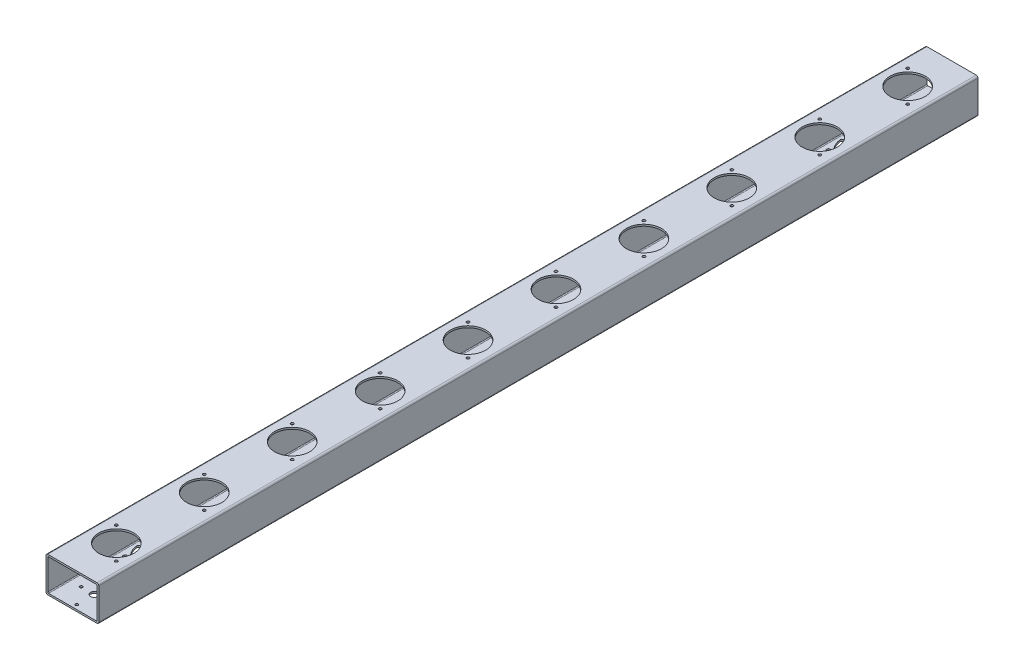
SolidWorks part; units mm, degrees
ref_plane "Plan de face" through (0, 0, 0) normal (0, 0, 1) x (1, 0, 0)
ref_plane "Plan de dessus" through (0, 0, 0) normal (0, 1, 0) x (1, 0, 0)
ref_plane "Plan de droite" through (0, 0, 0) normal (1, 0, 0) x (0, 0, -1)
sketch "Esquisse1" plane through (0, 0, 0) normal (0, 0, 1) x (1, 0, 0)
  line L0 (2, 2) -> (58, 2)
  line L1 (0, 0) -> (60, 0)
  line L2 (0, 0) -> (0, 40)
  line L3 (0, 40) -> (60, 40)
  line L4 (60, 0) -> (60, 40)
  line L5 (58, 2) -> (58, 38)
  line L6 (2, 38) -> (58, 38)
  line L7 (2, 2) -> (2, 38)
  dimension "D1" = 60
  dimension "D2" = 40
  dimension "D3" = 2
extrude "Boss.-Extru.1" add sketch "Esquisse1" along normal blind 1000
fillet "Congé1" radius 1 4 edges at (58, 2, 500) (58, 38, 500) (2, 38, 500) (2, 2, 500)
fillet "Congé2" radius 2 4 edges at (60, 0, 500) (0, 0, 500) (60, 40, 500) (0, 40, 500)
sketch "Esquisse2" plane through (0, 40, 0) normal (0, 1, 0) x (1, 0, 0)
  line L0 (30, 0) -> (30, -50) construction
  line L1 (58, 0) -> (2, 0) construction
  circle A0 centre (30, -50) radius 20
  circle A1 centre (30, -150) radius 20
  circle A2 centre (30, -250) radius 20
  circle A3 centre (30, -350) radius 20
  circle A4 centre (30, -450) radius 20
  circle A5 centre (30, -550) radius 20
  circle A6 centre (30, -650) radius 20
  circle A7 centre (30, -750) radius 20
  circle A8 centre (30, -850) radius 20
  circle A9 centre (30, -950) radius 20
  dimension "D1" = 40
  dimension "D2" = 50
  dimension "D4" = 100
  dimension "D3" = 10
extrude "Enlèv. mat.-Extru.1" cut sketch "Esquisse2" against normal up to next
sketch "Esquisse3" plane through (0, 0, 0) normal (0, -1, 0) x (1, 0, 0)
  line L0 (30, 975) -> (30, 1000) construction
  line L1 (2, 1000) -> (58, 1000) construction
  line L2 (30, 25) -> (30, 0) construction
  line L3 (2, 0) -> (58, 0) construction
  line L4 (30, 975) -> (30, 25) construction
  circle A0 centre (30, 975) radius 4.25
  circle A1 centre (30, 25) radius 4.25
  circle A2 centre (30, 500) radius 4.25
  dimension "D2" = 8.5
  dimension "D1" = 25
extrude "Enlèv. mat.-Extru.2" cut sketch "Esquisse3" against normal up to next
sketch "Esquisse4" plane through (0, 40, 0) normal (0, 1, 0) x (1, 0, 0)
  line L0 (12.3223, -32.3223) -> (47.6777, -67.6777) construction
  line L1 (2, 0) -> (2, -1000) construction
  circle A0 centre (30, -50) radius 25 construction
  circle A1 centre (30, -50) radius 20 construction
  circle A2 centre (12.3223, -32.3223) radius 1.6
  circle A3 centre (47.6777, -67.6777) radius 1.6
  point P6 (30, -50)
  dimension "D1" = 50
  dimension "D3" = 3.2
  dimension "D2" = 45
extrude "Enlèv. mat.-Extru.3" cut sketch "Esquisse4" against normal up to next
sketch "Esquisse6" plane through (0, 0, 0) normal (0, -1, 0) x (-1, 0, 0)
  line L0 (-20, -400) -> (-40, -400) construction
  line L1 (0, -400) -> (-20, -400) construction
  line L3 (0, 0) -> (0, -1000) construction
  line L4 (-40, -400) -> (-60, -400) construction
  line L5 (-60, -1000) -> (-60, 0) construction
  line L6 (-30, -370) -> (-30, -400) construction
  line L7 (-30, -400) -> (-30, -430) construction
  circle A0 centre (-20, -400) radius 1.6
  circle A1 centre (-40, -400) radius 1.6
  circle A2 centre (-30, -350) radius 20 construction
  circle A3 centre (-30, -450) radius 20 construction
  dimension "D2" = 3.2
  dimension "D1" = 20
extrude "Enlèv. mat.-Extru.4" cut sketch "Esquisse6" against normal up to next
pattern_linear "Répétition linéaire1" count 3 spacing 200 along (0, 0, 1) count 2 spacing 200 along (0, 0, -1) of "Enlèv. mat.-Extru.4"
sketch "Esquisse7" plane through (0, 0, 0) normal (0, -1, 0) x (-1, 0, 0)
  line L0 (-15, -500) -> (-45, -500) construction
  line L1 (-15, -975) -> (-45, -975) construction
  line L2 (-15, -25) -> (-45, -25) construction
  circle A0 centre (-15, -25) radius 1.6
  circle A1 centre (-45, -25) radius 1.6
  circle A2 centre (-15, -500) radius 1.6
  circle A3 centre (-45, -500) radius 1.6
  circle A4 centre (-15, -975) radius 1.6
  circle A5 centre (-45, -975) radius 1.6
  point P2 (-30, -500)
  point P3 (-30, -975)
  point P7 (-30, -25)
  dimension "D1" = 3.2
  dimension "D2" = 30
extrude "Enlèv. mat.-Extru.5" cut sketch "Esquisse7" against normal up to next
pattern_linear "Répétition linéaire2" count 10 spacing 100 along (0, 0, 1) of "Enlèv. mat.-Extru.3"
sketch "Esquisse8" plane through (0, 0, 0) normal (0, -1, 0) x (-1, 0, 0)
  circle A0 centre (-38, -55.1826) radius 1.4
  circle A1 centre (-22, -55.1826) radius 1.4
  circle A2 centre (-22, -55.1826) radius 1.25 construction
  circle A3 centre (-38, -55.1826) radius 1.25 construction
  dimension "D1" = 2.8
sketch "Esquisse9" plane through (0, 0, 0) normal (0, -1, 0) x (1, 0, 0)
  circle A1 centre (30, 950) radius 9.5306 construction
  circle A2 centre (30, 950) radius 20 construction
  circle A3 centre (22, 955.18) radius 1.1
  circle A4 centre (38, 955.18) radius 1.1
  point P8 (36.7592, 956.6587)
  point P11 (24.1118, 952.6968)
  dimension "D1" = 2.2
  dimension "D2" = 5.18
  dimension "D3" = 16
extrude "Enlèv. mat.-Extru.6" cut sketch "Esquisse9" against normal up to next
pattern_linear "Répétition linéaire3" count 10 spacing 100 along (0, 0, -1) of "Enlèv. mat.-Extru.6"
sketch "Esquisse10" plane through (0, 0, 0) normal (0, -1, 0) x (1, 0, 0)
  line L0 (2, 0) -> (58, 0) construction
  line L1 (10, 80) -> (50, 80) construction
  line L2 (10, 80) -> (10, 120) construction
  line L3 (10, 120) -> (50, 120) construction
  line L4 (50, 80) -> (50, 120) construction
  line L6 (0, 100) -> (10, 100) construction
  line L7 (0, 0) -> (0, 1000) construction
  line L8 (50, 100) -> (60, 100) construction
  line L9 (60, 1000) -> (60, 0) construction
  circle A0 centre (10, 120) radius 2.1
  circle A1 centre (50, 120) radius 2.1
  circle A2 centre (50, 80) radius 2.1
  circle A3 centre (10, 80) radius 2.1
  dimension "D2" = 4.2
  dimension "D1" = 40
  dimension "D3" = 100
extrude "Enlèv. mat.-Extru.7" cut sketch "Esquisse10" against normal up to next
pattern_linear "Répétition linéaire4" count 2 spacing 800 along (0, 0, 1) of "Enlèv. mat.-Extru.7"
sketch "Esquisse11" plane through (0, 0, 0) normal (0, -1, 0) x (1, 0, 0)
  line L1 (30, 910) -> (30, 916) construction
  line L2 (30, 918) -> (30, 924) construction
  line L3 (12.0278, 899) -> (6.0208, 899)
  line L4 (20.0501, 899) -> (14.0313, 899)
  line L6 (20.0501, 901) -> (14.0313, 901)
  line L8 (12.0278, 901) -> (6.0208, 901)
  line L9 (20.0501, 901) -> (20.0501, 899) construction
  line L10 (38.1201, 916.0644) -> (41.1236, 921.2666)
  line L11 (39.8521, 915.0644) -> (42.8556, 920.2666)
  line L12 (35.841, 908.1168) -> (38.8504, 913.3293)
  line L13 (34.1089, 909.1168) -> (37.1183, 914.3293)
  line L14 (39.8521, 884.9356) -> (42.8556, 879.7334)
  line L15 (38.1201, 883.9356) -> (41.1236, 878.7334)
  line L16 (34.1089, 890.8832) -> (37.1183, 885.6707)
  line L17 (35.841, 891.8832) -> (38.8504, 886.6707)
  arc A0 (41.1236, 921.2666) -> (42.8556, 920.2666) centre (30, 900) ccw
  arc A1 (20.0501, 899) -> (34.1089, 890.8832) centre (30, 900) ccw
  arc A2 (14.0313, 899) -> (37.1183, 885.6707) centre (30, 900) ccw
  arc A3 (12.0278, 899) -> (38.1201, 883.9356) centre (30, 900) ccw
  arc A4 (24.1103, 908.0815) -> (20.0094, 900.434) centre (30, 900) ccw construction
  arc A5 (39.8521, 884.9356) -> (39.8521, 915.0644) centre (30, 900) ccw
  arc A6 (38.8504, 886.6707) -> (38.8504, 913.3293) centre (30, 900) ccw
  arc A7 (35.841, 891.8832) -> (35.841, 908.1168) centre (30, 900) ccw
  arc A8 (38.1201, 916.0644) -> (12.0278, 901) centre (30, 900) ccw
  arc A9 (37.1183, 914.3293) -> (14.0313, 901) centre (30, 900) ccw
  arc A10 (34.1089, 909.1168) -> (20.0501, 901) centre (30, 900) ccw
  dimension "D1" = 48
  dimension "D2" = 20
  dimension "D3" = 2
  dimension "D4" = 2
  dimension "D5" = 3
extrude "Enlèv. mat.-Extru.8" cut sketch "Esquisse11" against normal up to next contours A8 L10 A0 L8 | A3 L3 A0 L15 | A5 L14 A0 L11 | L4 A2 L16 A1 | A7 L17 A6 L12 | A10 L13 A9 L6
fillet "Congé3" radius 2 24 edges at (6.0208, 1, 899) (12.0278, 1, 899) (14.0313, 1, 899) (20.0501, 1, 899) (34.1089, 1, 890.8832) (37.1183, 1, 885.6707) (38.1201, 1, 883.9356) (41.1236, 1, 878.7334) (42.8556, 1, 879.7334) (38.8504, 1, 886.6707) (39.8521, 1, 884.9356) (35.841, 1, 891.8832) (39.8521, 1, 915.0644) (42.8556, 1, 920.2666) (35.841, 1, 908.1168) (38.8504, 1, 913.3293) (34.1089, 1, 909.1168) (37.1183, 1, 914.3293) (20.0501, 1, 901) (14.0313, 1, 901) (6.0208, 1, 901) (12.0278, 1, 901) (38.1201, 1, 916.0644) (41.1236, 1, 921.2666)
pattern_linear "Répétition linéaire5" count 2 spacing 800 along (0, 0, -1) of "Enlèv. mat.-Extru.8", "Congé3"
sketch "Esquisse12" plane through (0, 0, 0) normal (0, -1, 0) x (1, 0, 0)
  line L0 (38, 755.18) -> (38, 740.18) construction
  line L1 (10, 740.18) -> (50, 740.18) construction
  line L2 (10, 740.18) -> (10, 670.18) construction
  line L3 (10, 670.18) -> (50, 670.18) construction
  line L4 (50, 740.18) -> (50, 670.18) construction
  line L5 (22, 655.18) -> (22, 670.18) construction
  line L6 (10, 705.18) -> (0, 705.18) construction
  line L7 (50, 705.18) -> (60, 705.18) construction
  line L8 (60, 1000) -> (60, 0) construction
  line L9 (0, 0) -> (0, 1000) construction
  circle A0 centre (10, 740.18) radius 1.6
  circle A1 centre (50, 740.18) radius 1.6
  circle A2 centre (50, 670.18) radius 1.6
  circle A3 centre (10, 670.18) radius 1.6
  dimension "D1" = 3.2
  dimension "D2" = 40
  dimension "D3" = 70
extrude "Enlèv. mat.-Extru.9" cut sketch "Esquisse12" against normal up to next
sketch "Esquisse13" plane through (0, 0, 0) normal (0, -1, 0) x (1, 0, 0)
  line L0 (17, 722.18) -> (0, 722.18) construction
  line L1 (17, 729.18) -> (43, 729.18)
  line L2 (17, 729.18) -> (17, 715.18)
  line L3 (17, 715.18) -> (43, 715.18)
  line L4 (43, 729.18) -> (43, 715.18)
  line L5 (0, 0) -> (0, 1000) construction
  line L6 (43, 722.18) -> (60, 722.18) construction
  line L7 (60, 1000) -> (60, 0) construction
  line L9 (30, 705.18) -> (30, 715.18) construction
  line L10 (17, 705.18) -> (30, 705.18) construction
  line L11 (30, 705.18) -> (43, 705.18) construction
  circle A0 centre (17, 705.18) radius 1.9
  circle A1 centre (30, 705.18) radius 1.9
  circle A2 centre (43, 705.18) radius 1.9
  circle A3 centre (10, 740.18) radius 1.6 construction
  dimension "D6" = 3.8
  dimension "D3" = 18
  dimension "D1" = 26
  dimension "D2" = 14
  dimension "D4" = 13
  dimension "D5" = 10
extrude "Enlèv. mat.-Extru.10" cut sketch "Esquisse13" against normal up to next
sketch "Esquisse14" plane through (0, 0, 0) normal (0, -1, 0) x (1, 0, 0)
  line L0 (30, 995) -> (30, 1000) construction
  line L1 (2, 1000) -> (58, 1000) construction
  line L2 (30, 5) -> (30, 0) construction
  line L3 (2, 0) -> (58, 0) construction
  circle A0 centre (30, 5) radius 1.6
  circle A1 centre (30, 995) radius 1.6
  dimension "D1" = 3.2
  dimension "D2" = 5
extrude "Enlèv. mat.-Extru.11" cut sketch "Esquisse14" against normal up to next
sketch "Esquisse15" plane through (0, 0, 0) normal (0, -1, 0) x (1, 0, 0)
  line L4 (20, 400) -> (40, 400) construction
  line L5 (30, 425) -> (30, 400) construction
  circle A3 centre (30, 425) radius 2.5
  dimension "D3" = 5
  dimension "D4" = 25
extrude "Enlèv. mat.-Extru.12" cut sketch "Esquisse15" against normal up to next
